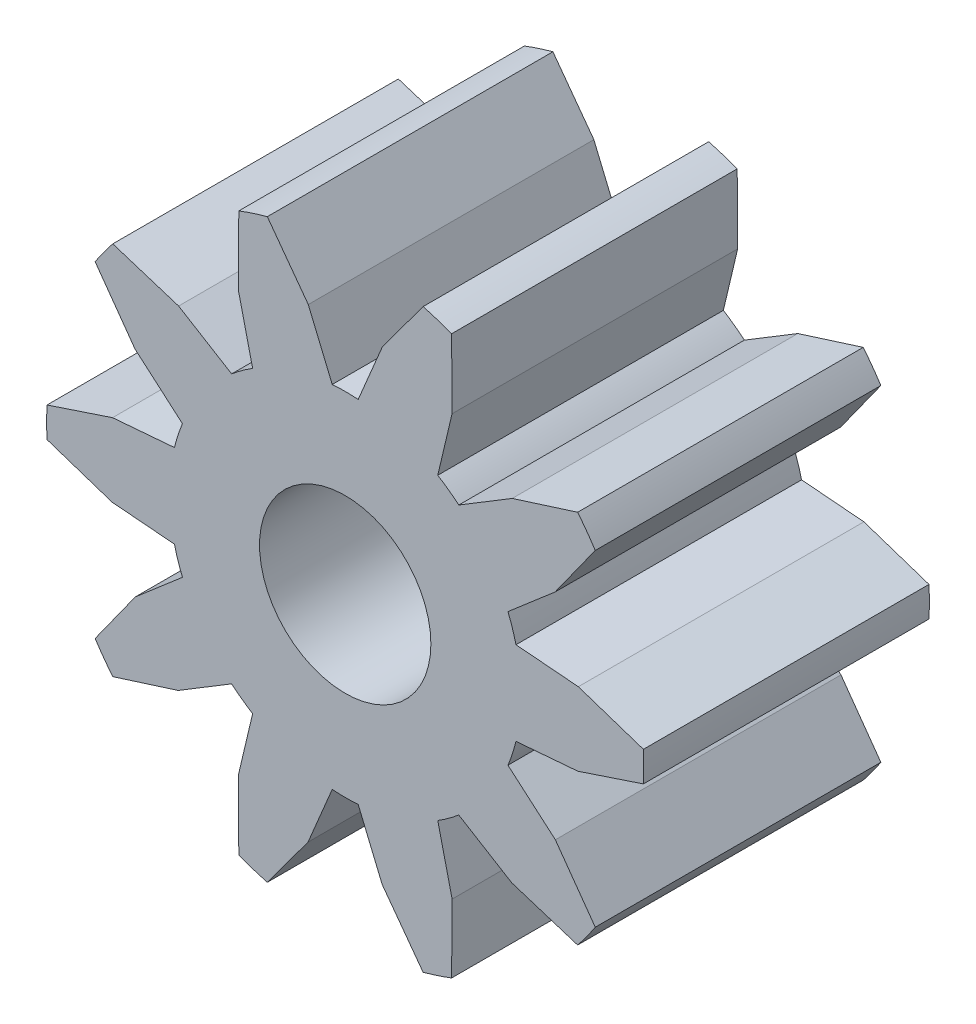
SolidWorks part; units mm, degrees
material "Titanium Ti-8Mn, Annealed"
ref_plane "Front Plane" through (0, 0, 0) normal (0, 0, 1) x (1, 0, 0)
ref_plane "Top Plane" through (0, 0, 0) normal (0, 1, 0) x (1, 0, 0)
ref_plane "Right Plane" through (0, 0, 0) normal (1, 0, 0) x (0, 0, -1)
sketch "Sketch1" plane through (0, 0, 0) normal (0, 0, 1) x (1, 0, 0)
  circle A0 centre (0, 0) radius 5.75
extrude "Boss-Extrude1" add sketch "Sketch1" along normal blind 5.5
sketch "Sketch2" plane through (0, 0, 5.5) normal (0, 0, 1) x (1, 0, 0)
  circle A0 centre (0, 0) radius 1.65
  dimension "D1" = 3.3
extrude "Cut-Extrude1" cut sketch "Sketch2" against normal blind 5.5
sketch "Sketch5" plane through (0, 0, 5.5) normal (0, 0, 1) x (1, 0, 0)
  line L0 (0, 0) -> (0, 8.0236) construction
  line L3 (-0.25, 3.3768) -> (-0.7112, 4.48)
  line L4 (-0.7112, 4.48) -> (-1.5, 5.5509)
  line L5 (0.25, 3.3768) -> (0.7158, 4.4879)
  line L6 (0.7158, 4.4879) -> (1.5, 5.5509)
  circle A1 centre (0, 0) radius 5.75 construction
  arc A2 (-1.5, 5.5509) -> (1.5, 5.5509) centre (0, 0) cw
  arc A3 (0.25, 3.3768) -> (-0.25, 3.3768) centre (0, 0) ccw
  dimension "D1" = 0.25
  dimension "D2" = 0.25
  dimension "D3" = 1.5
  dimension "D4" = 1.5
extrude "Cut-Extrude3" cut sketch "Sketch5" against normal blind 5.5
pattern_circular "CirPattern2" count 10 over 360 about axis through (0, 0, 0) along (0, 0, 1) of "Cut-Extrude3"
